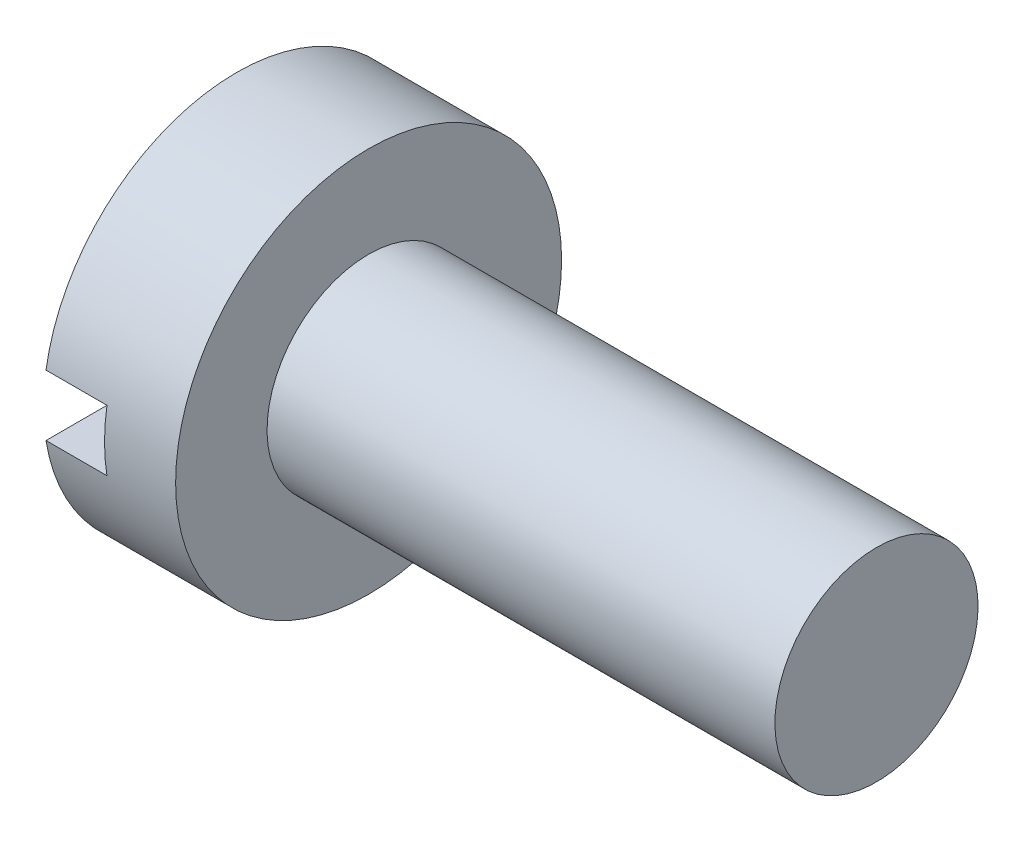
SolidWorks part; units mm, degrees
material "Plain Carbon Steel"
ref_plane "Front Plane" through (0, 0, 0) normal (0, 0, 1) x (1, 0, 0)
ref_plane "Top Plane" through (0, 0, 0) normal (0, 1, 0) x (1, 0, 0)
ref_plane "Right Plane" through (0, 0, 0) normal (1, 0, 0) x (0, 0, -1)
sketch "Sketch1" plane through (0, 0, 0) normal (0, 0, 1) x (1, 0, 0)
  line L0 (0, 0) -> (0, 1.9)
  line L1 (0, 1.9) -> (1.3, 1.9)
  line L2 (1.3, 1.9) -> (1.3, 1)
  line L3 (1.3, 1) -> (6.3, 1)
  line L4 (6.3, 1) -> (6.3, 0)
  line L5 (6.3, 0) -> (0, 0) construction
  line L6 (0, 0) -> (6.3, 0)
  dimension "D1" = 2
  dimension "D2" = 5
  dimension "D3" = 3.8
  dimension "D4" = 1.3
revolve "Revolve1" add sketch "Sketch1" angle 360 about L5
sketch "Sketch2" plane through (0, 0, 0) normal (-1, 0, 0) x (0, 0, 1)
  line L0 (1.9, 0) -> (-1.9, 0) construction
  line L1 (-1.9, 0.3) -> (1.9, 0.3)
  line L2 (-1.9, 0.3) -> (-1.9, -0.3)
  line L3 (-1.9, -0.3) -> (1.9, -0.3)
  line L4 (1.9, 0.3) -> (1.9, -0.3)
  circle A0 centre (0, 0) radius 1.9 construction
  dimension "D1" = 0.6
extrude "Cut-Extrude1" cut sketch "Sketch2" against normal blind 0.6
